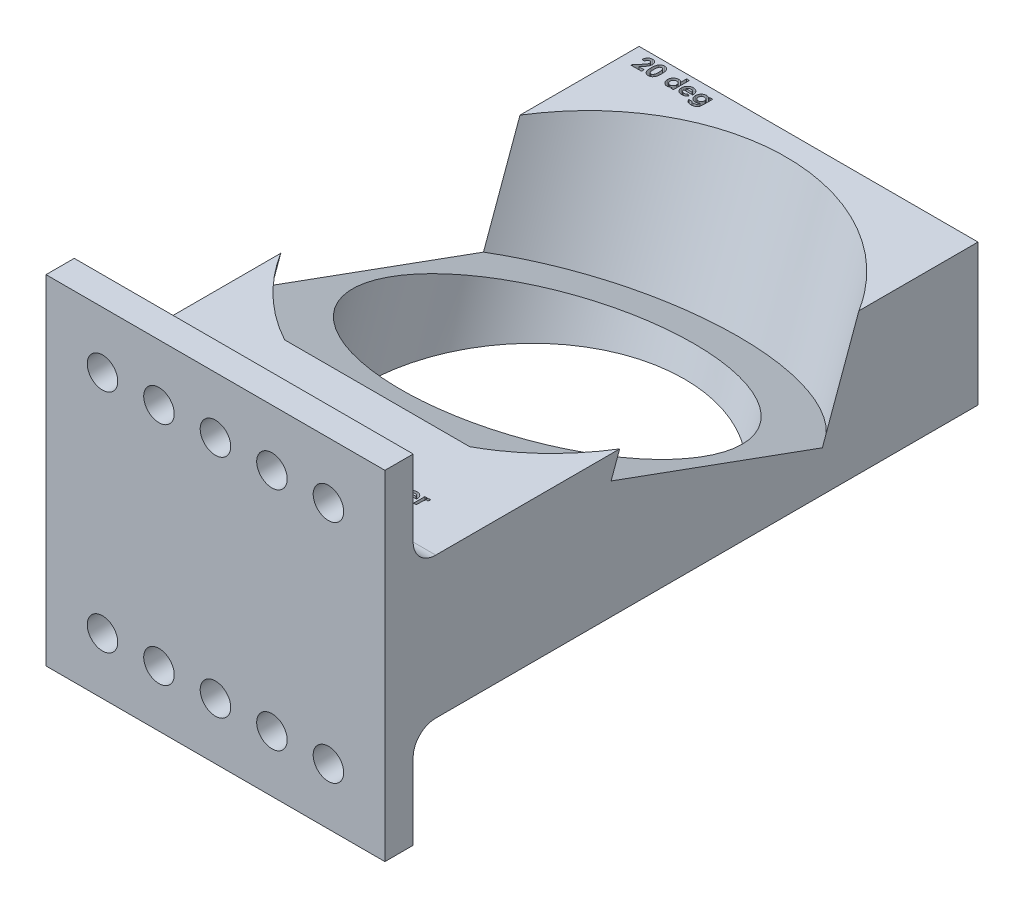
SolidWorks part; units mm, degrees
ref_plane "Front Plane" through (0, 0, 0) normal (0, 0, 1) x (1, 0, 0)
ref_plane "Top Plane" through (0, 0, 0) normal (0, 1, 0) x (1, 0, 0)
ref_plane "Right Plane" through (0, 0, 0) normal (1, 0, 0) x (0, 0, -1)
sketch "Sketch1" plane through (0, 0, 0) normal (1, 0, 0) x (0, 0, -1)
  line L1 (63.5, 15.875) -> (-63.5, 15.875)
  line L2 (63.5, 15.875) -> (63.5, -15.875)
  line L3 (63.5, -15.875) -> (-63.5, -15.875)
  line L4 (-63.5, 15.875) -> (-63.5, -15.875)
  line L5 (63.5, 15.875) -> (-63.5, -15.875) construction
  line L6 (63.5, -15.875) -> (-63.5, 15.875) construction
  point P0 (0, 0)
  dimension "D1" = 31.75
  dimension "D2" = 127
extrude "Boss-Extrude1" add sketch "Sketch1" along normal mid plane 76.2
sketch "Sketch2" plane through (0, 0, 0) normal (1, 0, 0) x (0, 0, -1)
  line L0 (0, -11.1285) -> (18.2185, 38.9265) construction
  line L1 (0, 0) -> (0, -41.4309) construction
  line L3 (37.6985, -10.038) -> (26.5881, -40.5635)
  line L4 (26.5881, -40.5635) -> (-6.35, -28.575)
  line L5 (-6.35, -28.575) -> (16.0568, 32.9872)
  line L8 (63.5, -15.875) -> (63.5, 15.875) construction
  line L9 (-63.5, -15.875) -> (63.5, -15.875) construction
  line L10 (37.6985, -10.038) -> (47.7231, -13.6867)
  line L11 (47.7231, -13.6867) -> (59.0195, 17.35)
  line L12 (59.0195, 17.35) -> (16.0568, 32.9872)
  dimension "D1" = 20
  dimension "D2" = 70.104
  dimension "D3" = 69.85
  dimension "D4" = 12.7
  dimension "D5" = 91.44
  dimension "D6" = 33.0285
  dimension "D7" = 32.4846
revolve "Cut-Revolve1" cut sketch "Sketch2" angle 360 about L0
sketch "Sketch3" plane through (0, 0, 63.5) normal (0, 0, 1) x (1, 0, 0)
  line L0 (38.1, 15.875) -> (38.1, -15.875) construction
  line L1 (-38.1, -38.1) -> (38.1, -38.1)
  line L2 (-38.1, -38.1) -> (-38.1, 38.1)
  line L3 (-38.1, 38.1) -> (38.1, 38.1)
  line L4 (38.1, -38.1) -> (38.1, 38.1)
  line L5 (-38.1, -38.1) -> (38.1, 38.1) construction
  line L6 (-38.1, 38.1) -> (38.1, -38.1) construction
  circle A0 centre (-25.4, 25.4) radius 3.429
  circle A1 centre (-12.7, 25.4) radius 3.429
  circle A2 centre (0, 25.4) radius 3.429
  circle A3 centre (12.7, 25.4) radius 3.429
  circle A4 centre (-12.7, -25.4) radius 3.429
  circle A5 centre (0, -25.4) radius 3.429
  circle A6 centre (12.7, -25.4) radius 3.429
  circle A7 centre (-25.4, -25.4) radius 3.429
  circle A8 centre (25.4, 25.4) radius 3.429
  circle A9 centre (25.4, -25.4) radius 3.429
  point P0 (0, 0)
  dimension "D2" = 6.858
  dimension "D1" = 76.2
  dimension "D3" = 12.7
  dimension "D4" = 12.7
  dimension "D5" = 5
  dimension "D6" = 2
extrude "Boss-Extrude2" add sketch "Sketch3" along normal blind 6.35
fillet "Fillet1" radius 5.08 2 edges at (0, 15.875, 63.5) (0, -15.875, 63.5)
sketch "Sketch4" plane through (0, 15.875, 0) normal (0, 1, 0) x (1, 0, 0)
  line L0 (-38.1, -50.8) -> (38.1, -50.8) construction
  line L1 (-38.1, -17.0661) -> (-38.1, -58.42) construction
  line L2 (38.1, -17.0661) -> (38.1, -58.42) construction
  line L3 (38.1, -69.85) -> (-38.1, -69.85) construction
  line L4 (-38.1, 58.928) -> (38.1, 58.928) construction
  line L5 (-38.1, 63.5) -> (-38.1, 36.7231) construction
  line L6 (38.1, 63.5) -> (38.1, 36.7231) construction
  line L7 (38.1, 63.5) -> (-38.1, 63.5) construction
  text T0 "<b>300 kHz Sangjin Holder</b>"
  text T1 "<b>  20 deg</b>"
  dimension "D1" = 19.05
  dimension "D2" = 4.572
extrude "Cut-Extrude1" cut sketch "Sketch4" against normal blind 2.54
